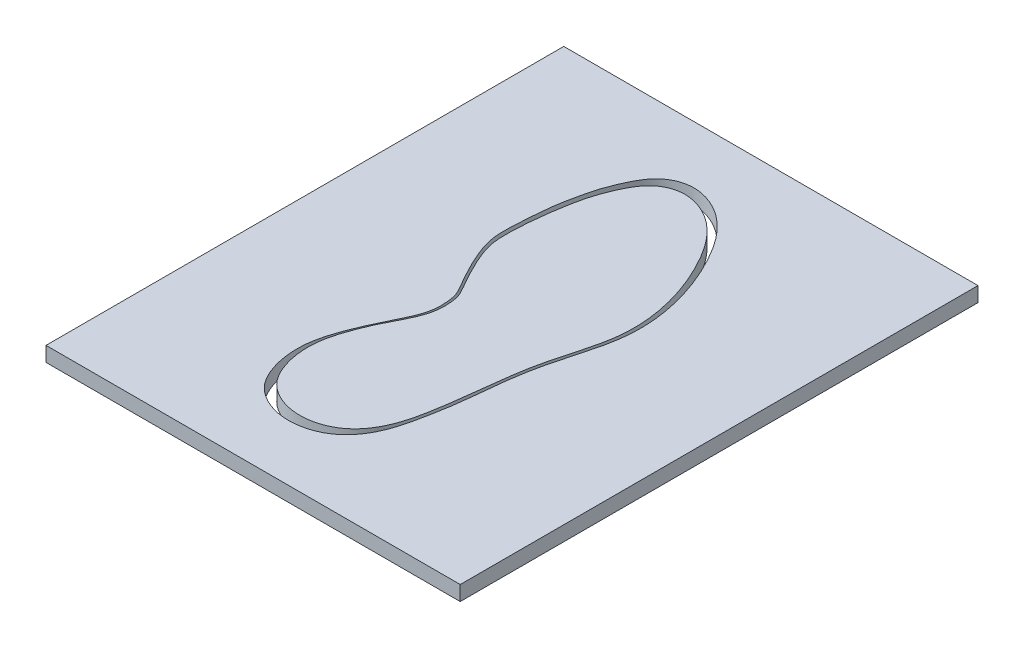
SolidWorks part; units mm, degrees
ref_plane "Front Plane" through (0, 0, 0) normal (0, 0, 1) x (1, 0, 0)
ref_plane "Top Plane" through (0, 0, 0) normal (0, 1, 0) x (1, 0, 0)
ref_plane "Right Plane" through (0, 0, 0) normal (1, 0, 0) x (0, 0, -1)
sketch "Sketch2" plane through (0, 0, 0) normal (0, 1, 0) x (1, 0, 0)
  line L0 (63.4495, 499.787) -> (317.2476, 499.787) construction
  line L1 (61.1015, 498.4987) -> (314.8995, 498.4987) construction
  line L3 (-86.8533, 334.8852) -> (193.1467, 334.8852)
  line L4 (-86.8533, 334.8852) -> (-86.8533, -15.1148)
  line L5 (-86.8533, -15.1148) -> (193.1467, -15.1148)
  line L6 (193.1467, 334.8852) -> (193.1467, -15.1148)
  line L7 (-86.8533, 334.8852) -> (193.1467, -15.1148) construction
  line L8 (-86.8533, -15.1148) -> (193.1467, 334.8852) construction
  spline S0 degree 3 poles (56.2408, 293.194) (41.4426, 297.0254) (30.3152, 294.7302) (22.4601, 290.0441) (16.5283, 282.0386) (11.7089, 271.8863) (7.8028, 261.3809) (5.7089, 251.3249) (3.2166, 240.2603) (1.928, 225.6738) (0.7127, 210.7509) (1.3142, 195.8387) (5.9677, 183.2432) (12.2303, 170.5692) (17.7962, 160.8729) (21.9893, 153.7588) (23.5554, 145.3172) (23.5973, 134.3951) (18.1549, 121.8123) (10.8844, 107.4675) (4.5352, 92.5688) (0.4223, 78.06) (-0.403, 64.5026) (1.7924, 50.2043) (10.05, 32.1568) (33.6159, 19.5662) (60.4876, 25.5095) (77.8252, 46.5102) (82.5493, 68.1315) (86.8882, 92.4141) (88.5385, 114.6993) (92.2312, 138.5739) (98.7794, 161.7516) (104.7629, 185.0084) (104.0687, 208.875) (98.4687, 233.6778) (87.7889, 258.273) (73.4257, 280.2573) (56.2408, 293.194) (41.4426, 297.0254) (30.3152, 294.7302) knots -0.098234 -0.05658 -0.026225 0 0.011197 0.025871 0.041353 0.056717 0.078087 0.093206 0.104404 0.130762 0.161071 0.174021 0.199736 0.22249 0.239778 0.251849 0.260384 0.279364 0.301615 0.323053 0.354375 0.376674 0.392737 0.417093 0.443448 0.481984 0.531425 0.557125 0.604876 0.631667 0.672152 0.70849 0.743679 0.784132 0.819354 0.853415 0.901766 0.94342 0.973775 1 1.011197 1.025871 1.041353 only from (38.2486, 296.0263) to (38.2486, 296.0263)
  point P6 (53.1467, 159.8852)
  point P86 (0, 0)
  point P87 (0, 0)
  dimension "D1" = 350
  dimension "D2" = 280
extrude "Boss-Extrude1" add sketch "Sketch2" along normal blind 10
sketch "Sketch3" plane through (0, 10, 0) normal (0, 1, 0) x (1, 0, 0)
  line L0 (-86.8533, 334.8852) -> (193.1467, -15.1148) construction
  line L1 (-86.8533, -15.1148) -> (193.1467, 334.8852) construction
  spline S0 degree 3 poles (56.1641, 286.5011) (42.1057, 290.1409) (31.5349, 287.9604) (24.072, 283.5087) (18.4391, 275.9031) (13.8504, 266.2603) (10.1872, 256.2713) (6.9005, 241.4743) (4.569, 224.6716) (3.4286, 208.176) (3.9787, 194.0167) (9.6421, 178.6578) (17.2469, 164.8419) (23.6229, 154.0385) (25.1236, 146.0186) (25.0099, 131.1575) (14.6074, 114.2322) (7.0844, 95.911) (3.1302, 82.1232) (2.3548, 69.2444) (4.4372, 55.6608) (12.2838, 38.5155) (34.6663, 26.5559) (60.2142, 32.1959) (76.6316, 52.1633) (83.3109, 80.8796) (86.2039, 111.4442) (90.3179, 139.6237) (96.5873, 161.6272) (102.2573, 183.7256) (101.6013, 206.3978) (96.2804, 229.9608) (86.1348, 253.3261) (72.4897, 274.2112) (56.1641, 286.5011) (42.1057, 290.1409) (31.5349, 287.9604) knots -0.098234 -0.05658 -0.026225 0 0.011197 0.025871 0.041353 0.056717 0.078087 0.093206 0.130762 0.161071 0.174021 0.199736 0.239778 0.251849 0.260384 0.279364 0.323053 0.354375 0.376674 0.392737 0.417093 0.443448 0.481984 0.531425 0.557125 0.604876 0.672152 0.70849 0.743679 0.784132 0.819354 0.853415 0.901766 0.94342 0.973775 1 1.011197 1.025871 1.041353 only from (39.0715, 289.1917) to (39.0715, 289.1917)
  point P8 (53.1467, 159.8852)
  point P11 (53.2247, 159.8577)
extrude "Boss-Extrude2" add sketch "Sketch3" against normal blind 10 separate body
